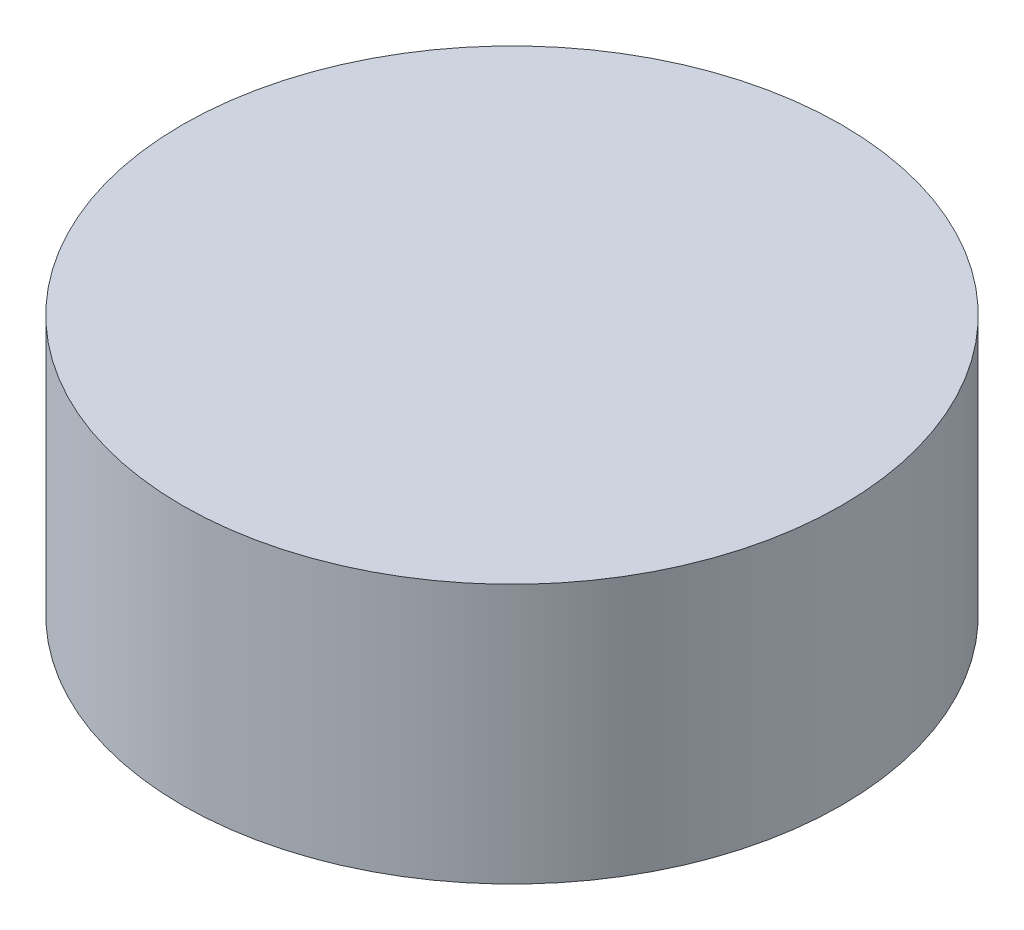
SolidWorks part; units mm, degrees
material "6061-T6 (SS)"
ref_plane "Front Plane" through (0, 0, 0) normal (0, 0, 1) x (1, 0, 0)
ref_plane "Top Plane" through (0, 0, 0) normal (0, 1, 0) x (1, 0, 0)
ref_plane "Right Plane" through (0, 0, 0) normal (1, 0, 0) x (0, 0, -1)
sketch "Sketch1" plane through (0, 0, 0) normal (0, 1, 0) x (1, 0, 0)
  circle A0 centre (0, 0) radius 6.35
  dimension "D1" = 12.7
extrude "Boss-Extrude1" add sketch "Sketch1" along normal blind 5
hole_wizard "Tap Drill for #4-40 Tap1" positions "Sketch2" profile "Sketch3" hole size "#4-40" standard "ANSI Inch"
sketch "Sketch2" plane through (0, 0, 0) normal (0, -1, 0) x (-1, 0, 0)
  point P0 (0, 0)
sketch "Sketch3" plane through (0, 0, 0) normal (1, 0, 0) x (0, 0, -1)
  line L0 (0, 0) -> (0, 2.9652)
  line L1 (0, 2.9652) -> (1.1303, 2.286)
  line L2 (1.1303, 2.286) -> (1.1303, 0)
  line L5 (1.1303, 0) -> (0, 0)
  line L10 (0, 2.9652) -> (-1.1303, 2.286) construction
  line L11 (0, -6.35) -> (0, 107.95) construction
  dimension "Hole Dia." = 2.2606
  dimension "Hole Depth" = 2.286
  dimension "Drill Angle" = 118
